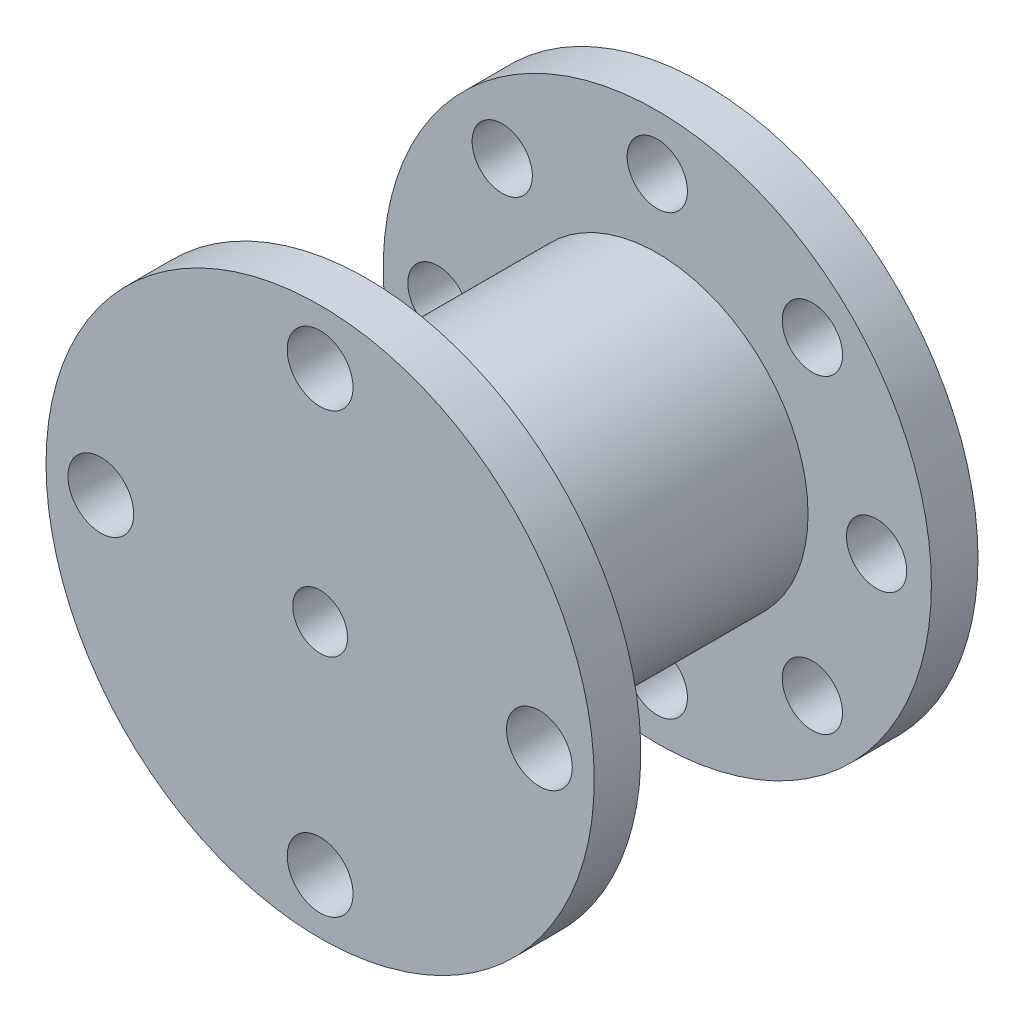
SolidWorks part; units mm, degrees
ref_plane "Plan de face" through (0, 0, 0) normal (0, 0, 1) x (1, 0, 0)
ref_plane "Plan de dessus" through (0, 0, 0) normal (0, 1, 0) x (1, 0, 0)
ref_plane "Plan de droite" through (0, 0, 0) normal (1, 0, 0) x (0, 0, -1)
sketch "Esquisse1" plane through (0, 0, 0) normal (0, 0, 1) x (1, 0, 0)
  line L0 (22.1497, 27.8802) -> (22.1497, 7.8802)
  line L1 (12.1497, 17.8802) -> (32.1497, 17.8802)
  line L2 (29.2207, 24.9512) -> (27.8065, 23.537)
  line L3 (29.2207, 24.9512) -> (15.0786, 10.8091)
  line L4 (15.0786, 24.9512) -> (29.2207, 10.8091)
  line L5 (22.1497, 27.8802) -> (22.1497, 26.4573)
  line L6 (22.1497, 27.8802) -> (22.1497, 25.8802)
  line L7 (15.0786, 24.9512) -> (16.4928, 23.537)
  line L8 (12.1497, 17.8802) -> (14.1497, 17.8802)
  line L9 (15.0786, 10.8091) -> (16.3763, 12.1068)
  line L10 (32.1497, 17.8802) -> (30.1497, 17.8802)
  line L11 (29.2207, 10.8091) -> (27.596, 12.4338)
  line L12 (22.1497, 7.8802) -> (22.1497, 9.6937)
  line L13 (29.2207, 10.8091) -> (27.8065, 12.2233)
  line L14 (22.1497, 7.8802) -> (22.1497, 9.8802)
  line L15 (15.0786, 10.8091) -> (16.6065, 12.337)
  line L16 (15.0786, 10.8091) -> (16.4928, 12.2233)
  line L17 (12.1497, 17.8802) -> (14.1497, 17.8802)
  circle A0 centre (22.1497, 17.8802) radius 10
  circle A1 centre (16.4928, 23.537) radius 1.1
  circle A2 centre (22.1497, 25.8802) radius 1.1
  circle A3 centre (27.8065, 23.537) radius 1.1
  circle A7 centre (30.1497, 17.8802) radius 1.1
  circle A9 centre (27.8065, 12.2233) radius 1.1
  circle A10 centre (22.1497, 9.8802) radius 1.1
  circle A12 centre (16.4928, 12.2233) radius 1.1
  circle A13 centre (14.1497, 17.8802) radius 1.1
extrude "Boss.-Extru.1" add sketch "Esquisse1" along normal blind 3 contours A3 L2 A0 L0 A2 L3 | A2 L0 A0 L4 A1 | A7 L10 A0 L2 A3 L3 L1 | A13 L1 L4 A1 A0 | A9 L13 A0 L10 A7 L1 L4 | A10 L14 A0 L13 A9 L4 L0 | A12 L16 A0 L14 A10 L0 L3 | A13 L1 A0 L16 A12 L3
sketch "Esquisse2" plane through (0, 0, 0) normal (0, 0, -1) x (-1, 0, 0)
  line L0 (-22.1497, 27.8802) -> (-22.1497, 7.8802)
  line L1 (-32.1497, 17.8802) -> (-12.1497, 17.8802)
  circle A0 centre (-22.1497, 17.8802) radius 10 construction
  circle A1 centre (-22.1497, 17.8802) radius 4.5
extrude "Enlèv. mat.-Extru.2" cut sketch "Esquisse2" against normal blind 2 contours L1 A1 L0 | L0 A1 L1
sketch "Esquisse3" plane through (0, 0, 3) normal (0, 0, 1) x (1, 0, 0)
  line L0 (22.1497, 27.8802) -> (22.1497, 7.8802)
  line L1 (12.1497, 17.8802) -> (32.1497, 17.8802)
  circle A0 centre (22.1497, 17.8802) radius 10 construction
  circle A1 centre (22.1497, 17.8802) radius 5.5
extrude "Boss.-Extru.2" add sketch "Esquisse3" along normal blind 8 contours L0 A1 L1 | L1 A1 L0 | L0 A1 L1 | L1 A1 L0
sketch "Esquisse4" plane through (0, 0, 11) normal (0, 0, 1) x (1, 0, 0)
  line L0 (22.1497, 23.3802) -> (22.1497, 12.3802)
  line L1 (27.6497, 17.8802) -> (16.6497, 17.8802)
  circle A0 centre (22.1497, 17.8802) radius 5.5 construction
  circle A1 centre (22.1497, 17.8802) radius 5.5 construction
  circle A2 centre (22.1497, 17.8802) radius 10
  circle M1 centre (22.1497, 17.8802) radius 5.5
extrude "Boss.-Extru.3" add sketch "Esquisse4" along normal blind 3 contours L1 L0 M1 | L1 L0 M1 | L1 L0 M1 | L0 L1 M1 | A2 M1
sketch "Esquisse5" plane through (0, 0, 14) normal (0, 0, 1) x (1, 0, 0)
  line L0 (22.1497, 27.8802) -> (22.1497, 7.8802)
  line L1 (12.1497, 17.8802) -> (32.1497, 17.8802)
  line L2 (22.1497, 27.8802) -> (22.1497, 25.8802)
  line L3 (32.1497, 17.8802) -> (30.1497, 17.8802)
  line L4 (22.1497, 7.8802) -> (22.1497, 9.8802)
  line L5 (12.1497, 17.8802) -> (14.1497, 17.8802)
  circle A0 centre (22.1497, 17.8802) radius 10 construction
  circle A1 centre (14.1497, 17.8802) radius 1.2
  circle A2 centre (22.1497, 25.8802) radius 1.2
  circle A3 centre (30.1497, 17.8802) radius 1.2
  circle A4 centre (22.1497, 9.8802) radius 1.2
extrude "Enlèv. mat.-Extru.3" cut sketch "Esquisse5" against normal blind 3 contours L1 A3 | L1 A3 | A4 | A2 | A1
sketch "Esquisse6" plane through (0, 0, 14) normal (0, 0, 1) x (1, 0, 0)
  line L0 (22.1497, 27.8802) -> (22.1497, 7.8802)
  line L1 (12.1497, 17.8802) -> (32.1497, 17.8802)
  circle A0 centre (22.1497, 17.8802) radius 10 construction
  circle A1 centre (22.1497, 17.8802) radius 1
extrude "Enlèv. mat.-Extru.4" cut sketch "Esquisse6" against normal blind 14 contours L1 A1 L0 | L0 A1 L1 | L1 A1 L0 | L0 A1 L1
sketch "Esquisse7" plane through (0, 0, 3) normal (0, 0, 1) x (1, 0, 0)
  line L0 (22.1497, 27.8802) -> (22.1497, 7.8802)
  circle A0 centre (22.1497, 17.8802) radius 10 construction
  circle A2 centre (27.8065, 23.537) radius 1.1
  circle A3 centre (30.1497, 17.8802) radius 1.1
  circle A4 centre (27.8065, 12.2233) radius 1.1
  circle A5 centre (22.1497, 9.8802) radius 1.1
  circle A6 centre (16.4928, 12.2233) radius 1.1
  circle A7 centre (14.1497, 17.8802) radius 1.1
  circle A8 centre (16.4928, 23.537) radius 1.1
  circle A9 centre (22.1497, 25.8802) radius 1.1
  circle A10 centre (22.1497, 17.8802) radius 5.5
  circle M2 centre (22.1497, 17.8802) radius 5.5
  circle M3 centre (22.1497, 17.8802) radius 10
  circle M4 centre (16.4928, 12.2233) radius 1.1
  circle M5 centre (22.1497, 9.8802) radius 1.1
  circle M6 centre (14.1497, 17.8802) radius 1.1
  circle M7 centre (16.4928, 23.537) radius 1.1
  circle M8 centre (27.8065, 12.2233) radius 1.1
  circle M9 centre (27.8065, 23.537) radius 1.1
  circle M10 centre (22.1497, 25.8802) radius 1.1
  circle M11 centre (30.1497, 17.8802) radius 1.1
extrude "Enlèv. mat.-Extru.5" cut sketch "Esquisse7" against normal blind 1.3 contours L0 M3 M5 M2 M10 M7 M6 M4 | L0 M3 M10 M2 M5 M8 M11 M9
sketch "Esquisse8" plane through (0, 0, 2) normal (0, 0, -1) x (-1, 0, 0)
  line L0 (-17.8883, 19.3262) -> (-26.411, 16.4341)
  circle A0 centre (-22.1497, 17.8802) radius 4.5 construction
  circle A1 centre (-22.1497, 17.8802) radius 4.5
  circle M1 centre (-22.1497, 17.8802) radius 1
  circle M2 centre (-22.1497, 17.8802) radius 4.5
extrude "Enlèv. mat.-Extru.6" cut sketch "Esquisse8" against normal blind 1 contours L0 M2 M1 | L0 M2 M1
sketch "Esquisse9" plane through (0, 0, 11) normal (0, 0, -1) x (-1, 0, 0)
  line L0 (-12.1497, 17.8802) -> (-32.1497, 17.8802)
  line L1 (-32.1497, 17.8802) -> (-22.1497, 7.8802)
  line L2 (-22.1497, 7.8802) -> (-22.1497, 27.8802)
  circle A0 centre (-22.1497, 17.8802) radius 10 construction
  circle A1 centre (-14.1497, 17.8802) radius 1.2
  circle A2 centre (-22.1497, 9.8802) radius 1.2
  circle A3 centre (-30.1497, 17.8802) radius 1.2
  circle A4 centre (-22.1497, 25.8802) radius 1.2
  circle A5 centre (-22.1497, 17.8802) radius 5.5
  circle M4 centre (-30.1497, 17.8802) radius 1.2
  circle M5 centre (-22.1497, 9.8802) radius 1.2
  circle M6 centre (-22.1497, 25.8802) radius 1.2
  circle M7 centre (-14.1497, 17.8802) radius 1.2
  circle M8 centre (-22.1497, 17.8802) radius 5.5
  circle M9 centre (-22.1497, 17.8802) radius 10
extrude "Enlèv. mat.-Extru.7" cut sketch "Esquisse9" against normal blind 1.3 contours L2 L0 M8 M6 M9 M4 | L1 L2 L0 M5 M8 M4 | L1 M9 | L2 L0 M9 M7 M8 M5 | L2 L0 M8 M7 M9 M6
